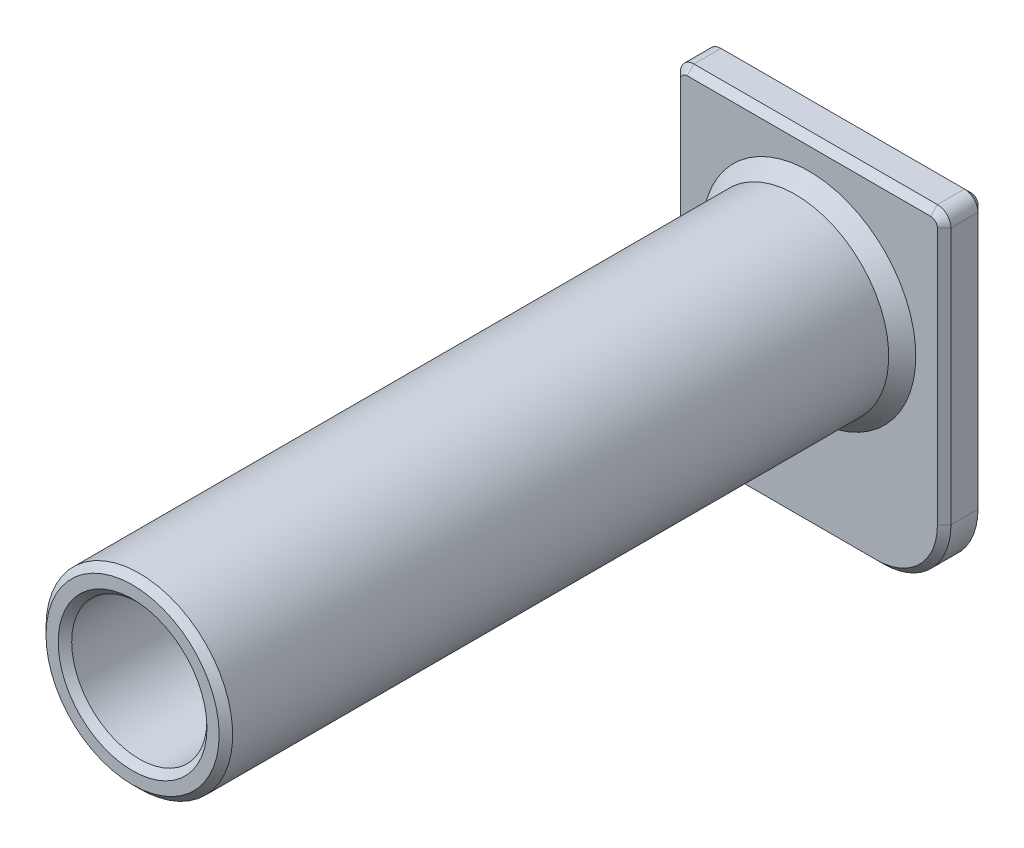
SolidWorks part; units mm, degrees
ref_plane "Front Plane" through (0, 0, 0) normal (0, 0, 1) x (1, 0, 0)
ref_plane "Top Plane" through (0, 0, 0) normal (0, 1, 0) x (1, 0, 0)
ref_plane "Right Plane" through (0, 0, 0) normal (1, 0, 0) x (0, 0, -1)
sketch "Sketch2" plane through (0, 0, 0) normal (0, 0, 1) x (1, 0, 0)
  line L0 (111.7654, 138.8608) -> (111.7654, 113.8608) construction
  line L1 (102.7654, 138.8608) -> (120.7654, 138.8608)
  line L2 (101.7654, 137.8608) -> (101.7654, 118.8608)
  line L3 (106.7654, 113.8608) -> (116.7654, 113.8608)
  line L4 (121.7654, 137.8608) -> (121.7654, 118.8608)
  line L5 (121.7654, 128.3608) -> (101.7654, 128.3608) construction
  line L6 (101.7654, 128.8608) -> (121.7654, 128.8608) construction
  circle A0 centre (111.7654, 128.8608) radius 4.75
  circle A1 centre (111.7654, 128.8608) radius 6.9
  arc A2 (116.7654, 113.8608) -> (121.7654, 118.8608) centre (116.7654, 118.8608) ccw
  arc A3 (101.7654, 118.8608) -> (106.7654, 113.8608) centre (106.7654, 118.8608) ccw
  arc A4 (120.7654, 138.8608) -> (121.7654, 137.8608) centre (120.7654, 137.8608) cw
  arc A5 (102.7654, 138.8608) -> (101.7654, 137.8608) centre (102.7654, 137.8608) ccw
  point P15 (121.7654, 113.8608)
  point P18 (101.7654, 113.8608)
  point P21 (121.7654, 138.8608)
  dimension "D4" = 9.5
  dimension "D5" = 13.8
  dimension "D6" = 5
  dimension "D7" = 1
  dimension "D1" = 25
  dimension "D2" = 20
  dimension "D3" = 10
extrude "Boss-Extrude1" add sketch "Sketch2" along normal blind 3 contours L1 A5 L2 A3 L3 A2 L4 A4 A1
sketch "Sketch3" plane through (0, 0, 0) normal (0, 0, 1) x (1, 0, 0)
  circle A0 centre (111.7654, 128.8608) radius 5
  circle A1 centre (111.7654, 128.8608) radius 6.9
extrude "Boss-Extrude2" add sketch "Sketch3" along normal blind 53
chamfer "Chamfer1" distance 0.5 angle 45 19 edges at (121.4725, 138.5679, 3) (121.7654, 128.3608, 3) (120.301, 115.3253, 3) (111.7654, 113.8608, 3) (103.2299, 115.3253, 3) (101.7654, 128.3608, 3) (102.0583, 138.5679, 3) (111.7654, 138.8608, 3) (116.7654, 128.8608, 0) (102.0583, 138.5679, 0) (101.7654, 128.3608, 0) (103.2299, 115.3253, 0) (111.7654, 113.8608, 0) (120.301, 115.3253, 0) (121.7654, 128.3608, 0) (121.4725, 138.5679, 0) (111.7654, 138.8608, 0) (116.7654, 128.8608, 53) (118.6654, 128.8608, 53)
chamfer "Chamfer2" distance 1 angle 45 1 edges at (118.6654, 128.8608, 3)
